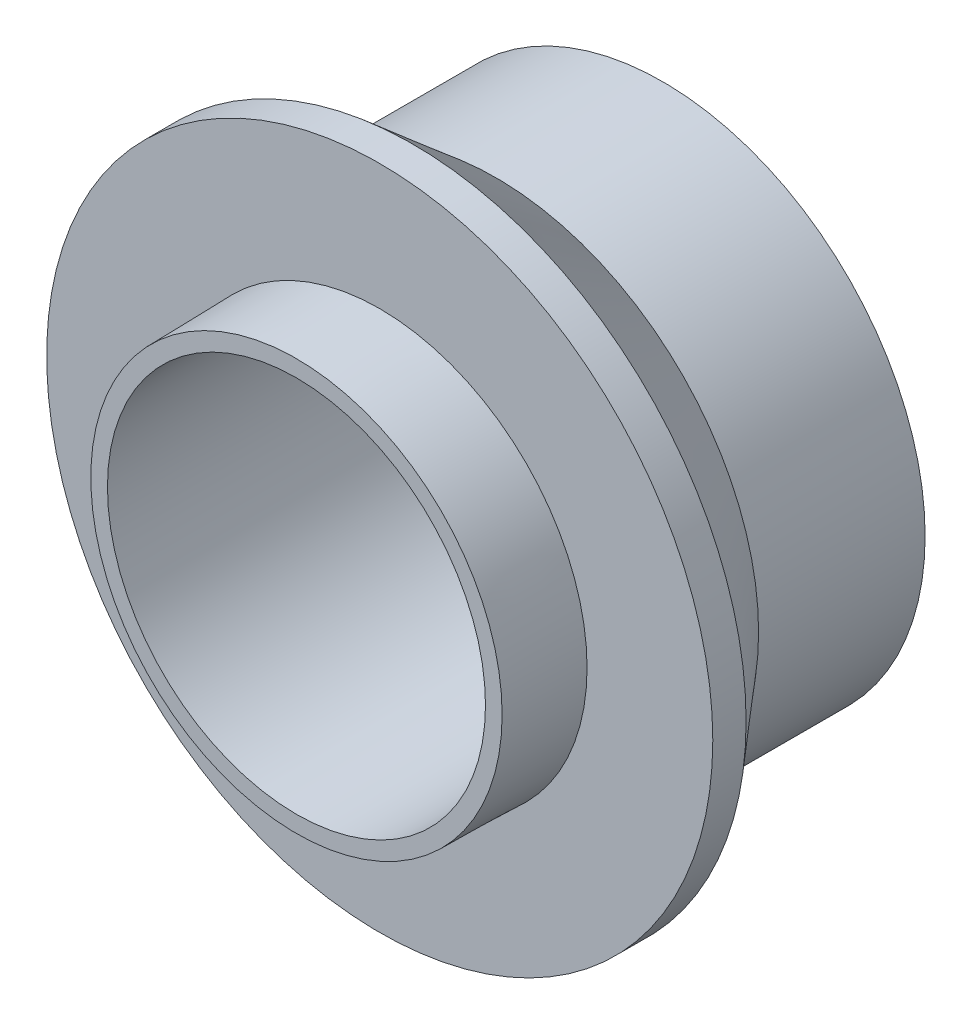
SolidWorks part; units mm, degrees
ref_plane "前视基准面" through (0, 0, 0) normal (0, 0, 1) x (1, 0, 0)
ref_plane "上视基准面" through (0, 0, 0) normal (0, 1, 0) x (1, 0, 0)
ref_plane "右视基准面" through (0, 0, 0) normal (1, 0, 0) x (0, 0, -1)
sketch "草图10" plane through (0, 0, 0) normal (0, 0, 1) x (1, 0, 0)
  circle A0 centre (0, 0) radius 15.75
  dimension "D1" = 31.5
extrude "凸台-拉伸5" add sketch "草图10" along normal blind 10
sketch "草图11" plane through (0, 0, 10) normal (0, 0, 1) x (1, 0, 0)
  circle A0 centre (0, 0) radius 15.75
ref_plane "基准面3" through (0, 0, 15) normal (0, 0, 1) x (1, 0, 0)
sketch "草图12" plane through (0, 0, 15) normal (0, 0, 1) x (1, 0, 0)
  circle A0 centre (0, 0) radius 20
  dimension "D1" = 40
loft "放样5" add profiles "草图12" section "草图12" section edge at (15.75, 0, 10)
sketch "草图14" plane through (0, 0, 15) normal (0, 0, 1) x (1, 0, 0)
  circle A0 centre (0, 0) radius 20
extrude "凸台-拉伸6" add sketch "草图14" along normal blind 2
sketch "草图15" plane through (0, 0, 17) normal (0, 0, 1) x (1, 0, 0)
  circle A0 centre (0, 0) radius 12.45
  dimension "D1" = 24.9
ref_plane "基准面4" through (0, 0, 22) normal (0, 0, 1) x (1, 0, 0)
sketch "草图16" plane through (0, 0, 22) normal (0, 0, 1) x (1, 0, 0)
  circle A0 centre (0, 0) radius 12.35
  dimension "D1" = 24.7
loft "放样6" add profiles "草图16", "草图15"
sketch "草图17" plane through (0, 0, 22) normal (0, 0, 1) x (1, 0, 0)
  circle A2 centre (0, 0) radius 11.35
  circle A3 centre (0, 0) radius 11.35
  dimension "D1" = 1
extrude "切除-拉伸3" cut sketch "草图17" against normal blind 30
